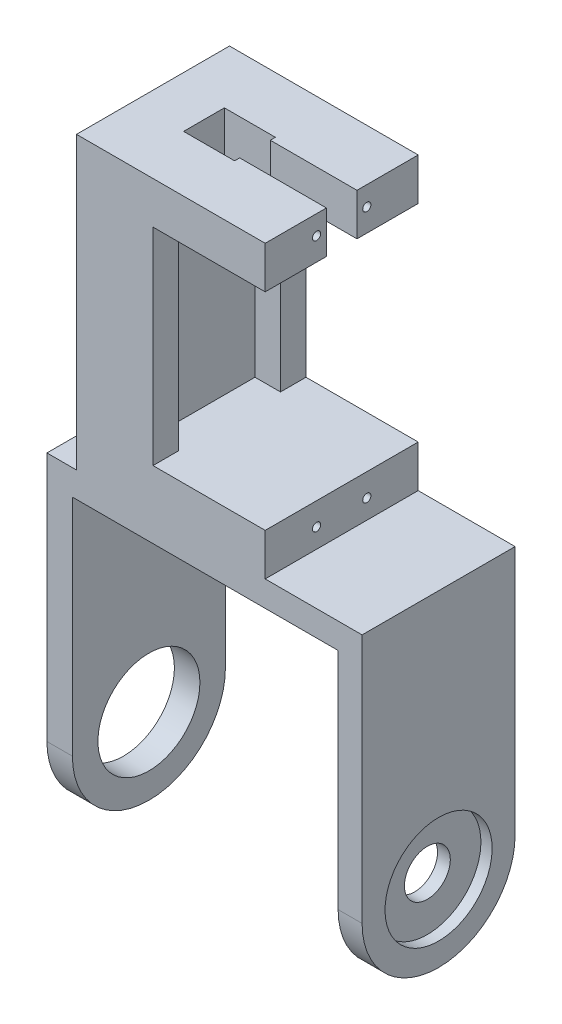
SolidWorks part; units mm, degrees
other "Marquage1"
sketch "Esquisse9" plane through (30.25, -27, 30) normal (0.9363, -0.2766, 0.2166) x (0.221, -0.0157, -0.9752)
ref_plane "Plan de face" through (0, 0, 0) normal (0, 0, 1) x (1, 0, 0)
ref_plane "Plan de dessus" through (0, 0, 0) normal (0, 1, 0) x (1, 0, 0)
ref_plane "Plan de droite" through (0, 0, 0) normal (1, 0, 0) x (0, 0, -1)
sketch "Esquisse1" plane through (0, 0, 0) normal (0, 0, 1) x (1, 0, 0)
  line L1 (-30.25, 32) -> (30.25, 32)
  line L2 (-30.25, 32) -> (-30.25, -32)
  line L3 (-30.25, -32) -> (30.25, -32)
  line L4 (30.25, 32) -> (30.25, -32)
  line L5 (-30.25, 32) -> (30.25, -32) construction
  line L6 (-30.25, -32) -> (30.25, 32) construction
  point P0 (0, 0)
  dimension "D1" = 60.5
  dimension "D2" = 64
extrude "Boss.-Extru.1" add sketch "Esquisse1" along normal blind 30
sketch "Esquisse2" plane through (30.25, 0, 0) normal (1, 0, 0) x (0, 0, -1)
  line L0 (-15, 32) -> (-15, -32) construction
  line L1 (-30, 32) -> (0, 32) construction
  line L2 (-30, -32) -> (0, -32) construction
  circle A0 centre (-15, -17) radius 4.5
  point P8 (-15, -17)
  dimension "D1" = 15
  dimension "D2" = 9
extrude "Enlèv. mat.-Extru.1" cut sketch "Esquisse2" against normal blind 32
sketch "Esquisse4" plane through (0, 0, 30) normal (0, 0, 1) x (1, 0, 0)
  line L0 (0, 0) -> (0, -11.7818) construction
  line L1 (-26.05, -56.5577) -> (26.05, -56.5577)
  line L2 (-26.05, -56.5577) -> (-26.05, 27)
  line L3 (-26.05, 27) -> (26.05, 27)
  line L4 (26.05, -56.5577) -> (26.05, 27)
  line L5 (30.25, 32) -> (-30.25, 32) construction
  line L6 (-30.25, 32) -> (-30.25, -32) construction
  dimension "D1" = 52.1
  dimension "D2" = 5
  dimension "D3" = 4.2
extrude "Enlèv. mat.-Extru.2" cut sketch "Esquisse4" against normal up to surface (30 mm away) up to face at (0, 0, 0)
sketch "Esquisse5" plane through (30.25, 0, 0) normal (1, 0, 0) x (0, 0, -1)
  circle A0 centre (-15, -17) radius 10.5
  dimension "D1" = 21
extrude "Enlèv. mat.-Extru.3" cut sketch "Esquisse5" against normal offset from surface (1.7 mm away) 2.5 up to face at (26.05, -12.5, 15)
sketch "Esquisse6" plane through (-26.05, 0, 0) normal (1, 0, 0) x (0, 0, -1)
  circle A0 centre (-15, -17) radius 10
extrude "Enlèv. mat.-Extru.4" cut sketch "Esquisse6" against normal up to surface (4.2 mm away) up to face at (-30.25, 0, 15)
sketch "Esquisse7" plane through (0, 0, 30) normal (0, 0, 1) x (1, 0, 0)
  line L0 (0, 0) -> (0, 32.5445) construction
  line L2 (-30.25, 32) -> (16.75, 32)
  line L3 (-30.25, 32) -> (-30.25, 89)
  line L4 (-30.25, 89) -> (16.75, 89)
  line L5 (16.75, 32) -> (16.75, 89)
  dimension "D1" = 57
  dimension "D2" = 47
extrude "Boss.-Extru.2" add sketch "Esquisse7" against normal up to surface (30 mm away) up to face at (0, -1.25, 0)
sketch "Esquisse8" plane through (0, 0, 30) normal (0, 0, 1) x (1, 0, 0)
  line L0 (-15.25, 90.392) -> (-15.25, 19.4965) construction
  line L1 (-30.25, 89) -> (-30.25, -32) construction
  line L2 (16.75, 60.5) -> (-55.9253, 60.5) construction
  line L3 (16.75, 32) -> (16.75, 89) construction
  line L4 (30.25, 32) -> (16.75, 32) construction
  line L6 (-15.25, 80.75) -> (11.75, 80.75)
  line L7 (-15.25, 80.75) -> (-15.25, 40.25)
  line L8 (-15.25, 40.25) -> (11.75, 40.25)
  line L10 (11.75, 40.25) -> (11.75, 32)
  line L11 (11.75, 98.5564) -> (21.75, 98.5564)
  line L12 (11.75, 98.5564) -> (11.75, 80.75)
  line L13 (11.75, 32) -> (21.75, 32)
  line L14 (21.75, 98.5564) -> (21.75, 32)
  dimension "D1" = 15
  dimension "D2" = 28.5
  dimension "D3" = 28.5
  dimension "D4" = 40.5
  dimension "D5" = 27
  dimension "D6" = 10
extrude "Enlèv. mat.-Extru.5" cut sketch "Esquisse8" against normal up to surface (30 mm away) up to face at (3.35, 16.8, 0)
sketch "Esquisse10" plane through (0, 80.75, 0) normal (0, -1, 0) x (1, 0, 0)
  line L0 (-1.75, 30) -> (-1.75, -1.0034) construction
  line L1 (-15.25, 15) -> (11.75, 15) construction
  line L2 (5.75, 0) -> (11.75, 0) construction
  line L4 (-15.25, 0) -> (11.75, 0)
  line L5 (11.75, 0) -> (11.75, 30)
  line L6 (11.75, 30) -> (-15.25, 30)
  line L7 (-15.25, 30) -> (-15.25, 0)
  line L8 (-15.25, 0) -> (-9.25, 0) construction
  line L9 (11.75, 0) -> (11.75, 30) construction
  line L10 (11.75, 30) -> (-15.25, 30) construction
  line L11 (-15.25, 30) -> (-15.25, 0) construction
  line L15 (-5.25, 11) -> (-5.25, 12)
  line L16 (-15.25, 19) -> (-5.25, 19)
  line L17 (-15.25, 19) -> (-15.25, 11)
  line L18 (-15.25, 11) -> (-5.25, 11)
  line L19 (34.75, 18) -> (34.75, 12)
  line L21 (-5.25, 19) -> (-5.25, 18)
  line L22 (-5.25, 18) -> (34.75, 18)
  line L24 (-5.25, 12) -> (34.75, 12)
  dimension "D2" = 6
  dimension "D4" = 10
  dimension "D1" = 0
extrude "Enlèv. mat.-Extru.6" cut sketch "Esquisse10" against normal up to surface (8.25 mm away) contours L17 L18 L15 L24 L19 L22 L21 L16 up to face at (-9.25, 89, 15)
sketch "Esquisse11" plane through (-15.25, 0, 0) normal (1, 0, 0) x (0, 0, -1)
  line L0 (-15, 103.0984) -> (-15, 64.9016) construction
  line L2 (0, 40.25) -> (-30, 40.25) construction
  line L3 (-30, 80.75) -> (-25, 80.75)
  line L4 (-30, 80.75) -> (-30, 40.25)
  line L5 (-30, 40.25) -> (-25, 40.25)
  line L6 (-25, 80.75) -> (-25, 40.25)
  line L7 (0, 40.25) -> (-5, 40.25)
  line L8 (-5, 80.75) -> (-5, 40.25)
  line L9 (0, 80.75) -> (-5, 80.75)
  line L10 (0, 80.75) -> (0, 40.25)
  point P3 (-15, 84)
  dimension "D1" = 5
extrude "Boss.-Extru.3" add sketch "Esquisse11" along normal blind 5
sketch "Esquisse12" plane through (11.75, 0, 0) normal (1, 0, 0) x (0, 0, -1)
  line L0 (-15, 89) -> (-15, 40.25) construction
  line L1 (-19, 89) -> (-11, 89) construction
  line L2 (0, 40.25) -> (-30, 40.25) construction
  line L3 (0, 80.75) -> (-12, 80.75) construction
  line L4 (-25, 60.5) -> (3.7732, 60.5) construction
  line L5 (-25, 40.25) -> (-25, 80.75) construction
  circle A0 centre (-19.925, 85.21) radius 0.5
  circle A1 centre (-10.075, 85.21) radius 0.5
  circle A2 centre (-10.075, 35.79) radius 0.5
  circle A3 centre (-19.925, 35.79) radius 0.5
  point P6 (-10.075, 85.21)
  point P9 (-19.925, 35.79)
  point P10 (-19.925, 85.21)
  point P15 (-10.075, 35.79)
  dimension "D3" = 1
  dimension "D1" = 4.46
  dimension "D2" = 4.925
  dimension "D4" = 4.925
  dimension "D5" = 4.46
extrude "Enlèv. mat.-Extru.7" cut sketch "Esquisse12" against normal blind 15
hole_wizard "Trou taraudé M2x0.42" positions "Esquisse3D2" profile "Esquisse14" tap size "M2x0.4" standard "Ansi Metric"
sketch3d "Esquisse3D2"
  line L0 (-3.25, 85.21, 19.925) -> (11.75, 85.21, 19.925) construction
  line L1 (-3.25, 85.21, 10.075) -> (11.75, 85.21, 10.075) construction
  line L2 (-3.25, 35.79, 10.075) -> (11.75, 35.79, 10.075) construction
  line L3 (-3.25, 35.79, 19.925) -> (11.75, 35.79, 19.925) construction
  point P0 (11.75, 85.21, 19.925)
  point P4 (11.75, 85.21, 10.075)
  point P8 (11.75, 35.79, 10.075)
  point P12 (11.75, 35.79, 19.925)
cosmetic thread "Filetage de perçage5" parameters "D1"=15, "D2"=2
cosmetic thread "Filetage de perçage6" parameters "D1"=15, "D2"=2
cosmetic thread "Filetage de perçage7" parameters "D1"=15, "D2"=2
cosmetic thread "Filetage de perçage8" parameters "D1"=15, "D2"=2
sketch "Esquisse14" plane through (11.75, 85.21, 19.925) normal (0, 1, 0) x (0, 0, -1)
  line L0 (0, 0) -> (0, 17.4807)
  line L1 (0, 17.4807) -> (0.8, 17)
  line L2 (0.8, 17) -> (0.8, 0)
  line L5 (0.8, 0) -> (0, 0)
  line L10 (0, 17.4807) -> (-0.8, 17) construction
  line L11 (0, -6.35) -> (0, 107.95) construction
  dimension "Diamètre du trou pour taraudage" = 1.6
  dimension "Profondeur du trou pour taraudage" = 17
  dimension "Angle de pointe" = 118
sketch "Esquisse15" plane through (-30.25, 0, 0) normal (-1, 0, 0) x (0, 0, 1)
  line L0 (30, -32) -> (0, -32) construction
  line L1 (40, -17) -> (30, -17)
  line L2 (0, -17) -> (-10, -17)
  arc A0 (5, -17) -> (25, -17) centre (15, -17) ccw construction
  arc A1 (0, -17) -> (30, -17) centre (15, -17) ccw
  arc A2 (-10, -17) -> (40, -17) centre (15, -17) ccw
  dimension "D1" = 20
  dimension "D2" = 50
extrude "Enlèv. mat.-Extru.8" cut sketch "Esquisse15" against normal up to surface (60.5 mm away) up to face at (30.25, -6.5, 15)
sketch "Esquisse17" plane through (-15.25, 0, 0) normal (1, 0, 0) x (0, 0, -1)
  line L0 (-15, 89) -> (-15, 40.25) construction
  line L1 (-19, 89) -> (-11, 89) construction
  line L2 (0, 40.25) -> (-30, 40.25) construction
  line L3 (-5, 70.15) -> (-34.9076, 70.15) construction
  line L4 (-5, 80.75) -> (-5, 40.25) construction
  line L5 (-25, 40.25) -> (-25, 80.75) construction
  line L6 (-5, 40.25) -> (-25, 40.25) construction
  circle A0 centre (-15, 70.15) radius 9.25
  point P14 (-15, 70.15)
  dimension "D1" = 10
  dimension "D2" = 29.9
sketch "Esquisse21" plane through (-30.25, 0, 0) normal (-1, 0, 0) x (0, 0, 1)
  circle A0 centre (15, 70.15) radius 9.25 construction
  circle A1 centre (15, 70.15) radius 9.25 construction
  circle A2 centre (15, 70.15) radius 1
  point P4 (15, 70.15)
hole_wizard "Trou taraudé M3x0.54" positions "Esquisse3D6" profile "Esquisse24" tap size "M3x0.5" standard "Ansi Metric"
sketch3d "Esquisse3D6"
  point P0 (-30.25, 70.15, 15)
sketch "Esquisse24" plane through (-30.25, 70.15, 15) normal (0, 1, 0) x (0, 0, 1)
  line L0 (0, 0) -> (0, 18.2511)
  line L1 (0, 18.2511) -> (1.25, 17.5)
  line L2 (1.25, 17.5) -> (1.25, 0)
  line L5 (1.25, 0) -> (0, 0)
  line L10 (0, 18.2511) -> (-1.25, 17.5) construction
  line L11 (0, -6.35) -> (0, 107.95) construction
  dimension "Diamètre du trou pour taraudage" = 2.5
  dimension "Profondeur du trou pour taraudage" = 17.5
  dimension "Angle de pointe" = 118
cosmetic thread "Filetage de perçage12" parameters "D1"=15, "D2"=3
sketch "Esquisse26" plane through (0, 0, 30) normal (0, 0, 1) x (1, 0, 0)
  line L0 (11.75, 32) -> (-30.25, 32) construction
  line L1 (-30.25, 89) -> (-30.25, -17) construction
  line L2 (-30.25, 96.5132) -> (-25.25, 96.5132)
  line L3 (-30.25, 96.5132) -> (-30.25, 32)
  line L4 (-30.25, 32) -> (-25.25, 32)
  line L5 (-25.25, 96.5132) -> (-25.25, 32)
  dimension "D1" = 5
extrude "Enlèv. mat.-Extru.9" cut sketch "Esquisse26" against normal up to surface (30 mm away) up to face at (1.8929, 33.5714, 0)
sketch "Esquisse27" plane through (-30.25, 0, 0) normal (-1, 0, 0) x (0, 0, 1)
  line L3 (30, -17) -> (30, 32)
  line L4 (30, 32) -> (0, 32)
  line L5 (0, 32) -> (0, -17)
  line L6 (30, -17) -> (30, 32)
  line L7 (30, 32) -> (0, 32)
  line L8 (0, 32) -> (0, -17)
  circle A0 centre (15, -17) radius 10 construction
  arc A1 (0, -17) -> (30, -17) centre (15, -17) ccw
  arc A2 (0, -17) -> (30, -17) centre (15, -17) ccw
  circle A3 centre (15, -17) radius 10
  dimension "D1" = 0
extrude "Boss.-Extru.4" add sketch "Esquisse27" along normal blind 0.8
sketch "Esquisse28" plane through (30.25, 0, 0) normal (1, 0, 0) x (0, 0, -1)
  line L3 (-30, 32) -> (-30, -17)
  line L4 (0, -17) -> (0, 32)
  line L5 (0, 32) -> (-30, 32)
  line L6 (-30, 32) -> (-30, -17)
  line L7 (0, -17) -> (0, 32)
  line L8 (0, 32) -> (-30, 32)
  circle A0 centre (-15, -17) radius 10.5 construction
  arc A1 (-30, -17) -> (0, -17) centre (-15, -17) ccw
  arc A2 (-30, -17) -> (0, -17) centre (-15, -17) ccw
  circle A3 centre (-15, -17) radius 10.5
  dimension "D1" = 0
extrude "Boss.-Extru.5" add sketch "Esquisse28" along normal blind 0.5
